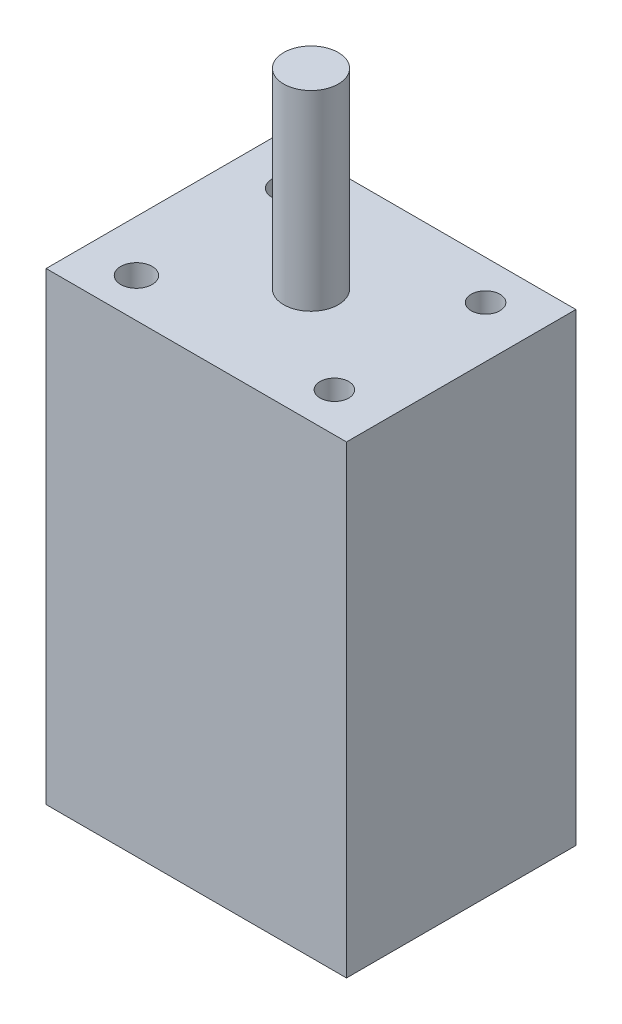
SolidWorks part; units mm, degrees
ref_plane "前视基准面" through (0, 0, 0) normal (0, 0, 1) x (1, 0, 0)
ref_plane "上视基准面" through (0, 0, 0) normal (0, 1, 0) x (1, 0, 0)
ref_plane "右视基准面" through (0, 0, 0) normal (1, 0, 0) x (0, 0, -1)
other "Configuration Table"
sketch "01_Housing_Profile" plane through (0, 0, 0) normal (0, 1, 0) x (1, 0, 0)
  line L1 (-27.5, -21) -> (27.5, -21)
  line L2 (-27.5, -21) -> (-27.5, 21)
  line L3 (-27.5, 21) -> (27.5, 21)
  line L4 (27.5, -21) -> (27.5, 21)
  line L5 (-27.5, -21) -> (27.5, 21) construction
  line L6 (-27.5, 21) -> (27.5, -21) construction
  circle A0 centre (-18.1228, -13.8392) radius 2.8773
  circle A1 centre (18.1228, -13.8392) radius 2.6272
  circle A2 centre (-18.1228, 13.8392) radius 2.8773
  circle A3 centre (18.1228, 13.8392) radius 2.6272
  point P0 (0, 0)
extrude "01_Housing_Block" add sketch "01_Housing_Profile" along normal blind 85
sketch "03_Output_Shaft_Profile" plane through (0, 0, 0) normal (0, 1, 0) x (1, 0, 0)
  circle A0 centre (0, 0) radius 5
extrude "03_Output_Shaft" add sketch "03_Output_Shaft_Profile" along normal blind 120
